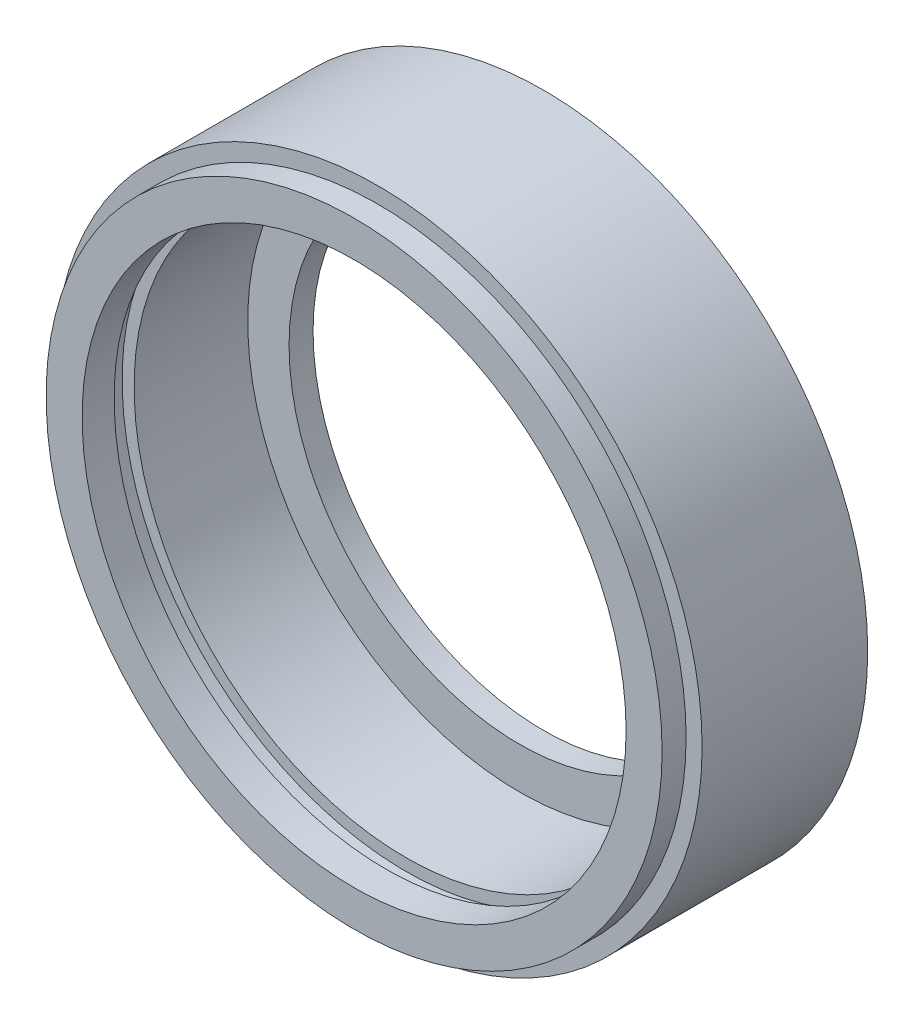
SolidWorks part; units mm, degrees
material "СТ3КП"
ref_plane "Спереди" through (0, 0, 0) normal (0, 0, 1) x (1, 0, 0)
ref_plane "Сверху" through (0, 0, 0) normal (0, 1, 0) x (1, 0, 0)
ref_plane "Справа" through (0, 0, 0) normal (1, 0, 0) x (0, 0, -1)
sketch "Эскиз1" plane through (0, 0, 0) normal (1, 0, 0) x (0, 0, -1)
  line L0 (0, 0) -> (0, 40.5) construction
  line L1 (-23.7, 0) -> (-23.7, 225) construction
  line L2 (-23.7, 38.5) -> (-20.7, 38.5) construction
  line L3 (-20.7, 38.5) -> (-20.7, 40.5) construction
  line L4 (-23.7, 40.5) -> (0, 40.5) construction
  line L5 (0, 28.8333) -> (0, 40.5)
  line L6 (-23.7, 34) -> (-23.7, 38.5)
  line L7 (-23.7, 38.5) -> (-20.7, 38.5)
  line L8 (-20.7, 38.5) -> (-20.7, 40.5)
  line L9 (-20.7, 40.5) -> (0, 40.5)
  line L10 (-23.7, 34) -> (-19.7, 34)
  line L11 (-3, 34) -> (-3, 28.8333)
  line L12 (-3, 28.8333) -> (0, 28.8333)
  line L13 (-4.5, 34) -> (-16.5, 34) construction
  line L14 (-3, -32.5) -> (-3, 32.5) construction
  line L15 (-19.7, 35.5) -> (-19.7, -34.3561) construction
  line L16 (-19.7, 35.5) -> (-19.7, 34)
  line L17 (-19.7, 35.5) -> (-17.2, 35.5)
  line L18 (-17.2, 35.5) -> (-17.2, 34)
  line L19 (-17.2, 34) -> (-3, 34)
  line L20 (-3, 28.8333) -> (-5.5, 28.8333) construction
  line L21 (-1010.5, 0) -> (48989.5, 0) construction
  dimension "D1" = 2.5
revolve "Повернуть1" add sketch "Эскиз1" angle 360 about L21
